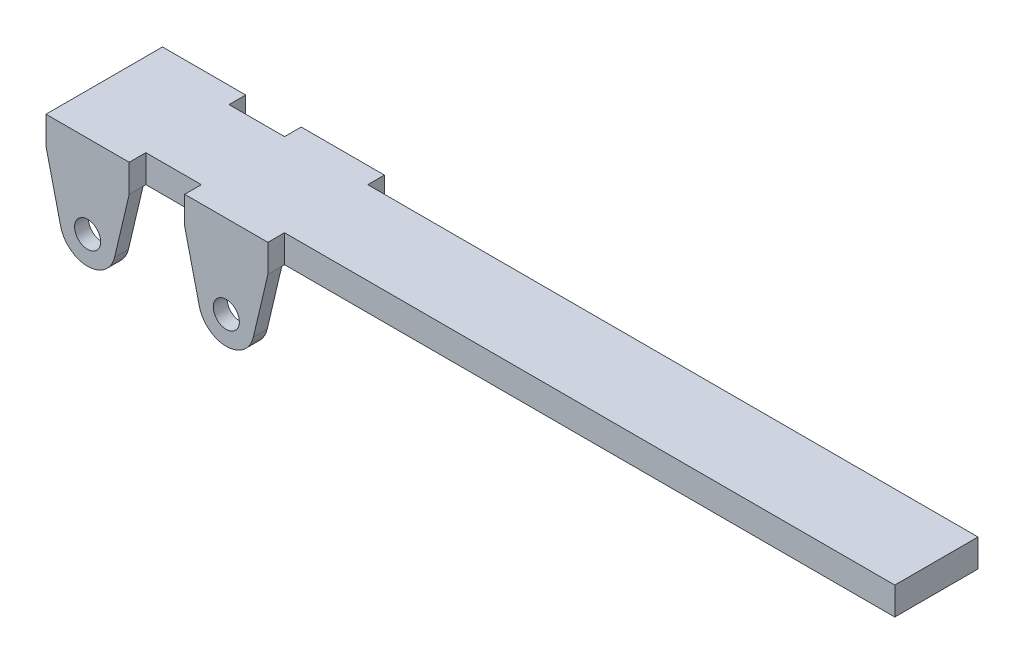
SolidWorks part; units mm, degrees
ref_plane "前视基准面" through (0, 0, 0) normal (0, 0, 1) x (1, 0, 0)
ref_plane "上视基准面" through (0, 0, 0) normal (0, 1, 0) x (1, 0, 0)
ref_plane "右视基准面" through (0, 0, 0) normal (1, 0, 0) x (0, 0, -1)
sketch "草图1" plane through (0, 0, 0) normal (0, 0, 1) x (1, 0, 0)
  line L0 (0, 0) -> (0, 5)
  line L1 (0, 5) -> (150, 5)
  line L2 (150, 5) -> (150, 0)
  line L3 (150, 0) -> (0, 0)
  dimension "D1" = 5
  dimension "D2" = 150
extrude "凸台-拉伸1" add sketch "草图1" along normal blind 15
sketch "草图2" plane through (0, 0, 15) normal (0, 0, 1) x (1, 0, 0)
  line L0 (0, 5) -> (0, 0)
  line L1 (0, 0) -> (2.6339, -11.1495)
  line L3 (12.3661, -11.1495) -> (15, 0)
  line L4 (15, 0) -> (15, 5)
  line L5 (150, 5) -> (0, 5) construction
  line L6 (15, 5) -> (0, 5)
  line L7 (0, 0) -> (150, 0) construction
  circle A0 centre (7.5, -10) radius 5
  circle A1 centre (7.5, -10) radius 2.35
  point P14 (2.6339, -11.1495)
  dimension "D2" = 10
  dimension "D5" = 4.7
  dimension "D1" = 10
  dimension "D3" = 15
  dimension "D4" = 7.5
extrude "凸台-拉伸2" add sketch "草图2" along normal blind 3
ref_plane "基准面4" through (0, 0, 7.5) normal (0, 0, -1) x (-1, 0, 0)
mirror "镜向1" about plane through (0, 0, 7.5) normal (0, 0, -1) of "凸台-拉伸2"
ref_plane "基准面5" through (20, 0, 0) normal (-1, 0, 0) x (0, 0, 1)
mirror "镜向2" about plane through (20, 0, 0) normal (-1, 0, 0) of "镜向1", "凸台-拉伸2"
sketch "草图3" plane through (0, 0, 0) normal (-1, 0, 0) x (0, 0, 1)
  line L0 (-0.5, 0) -> (15.5, 0)
  line L1 (-3, 0) -> (0, 0) construction
  line L2 (18, 0) -> (15, 0) construction
  line L3 (15.5, 0) -> (15.5, -20)
  line L4 (15.5, -20) -> (-0.5, -20)
  line L5 (-0.5, -20) -> (-0.5, 0)
  line L6 (0, 0) -> (0, -11.1495) construction
  line L7 (15, 0) -> (15, -11.1495) construction
  dimension "D1" = 0.5
  dimension "D2" = 0.5
  dimension "D3" = 20
extrude "切除-拉伸1" cut sketch "草图3" against normal blind 53
